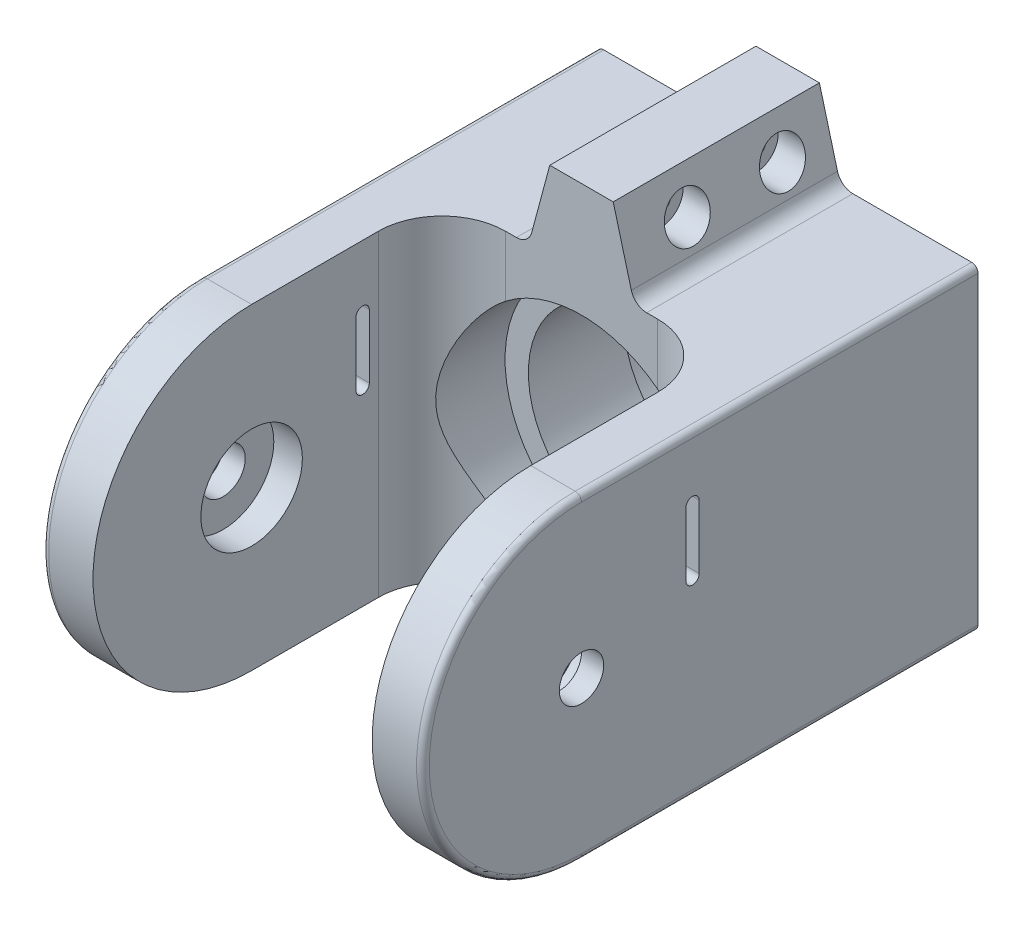
SolidWorks part; units mm, degrees
ref_plane "Front Plane" through (0, 0, 0) normal (0, 0, 1) x (1, 0, 0)
ref_plane "Top Plane" through (0, 0, 0) normal (0, 1, 0) x (1, 0, 0)
ref_plane "Right Plane" through (0, 0, 0) normal (1, 0, 0) x (0, 0, -1)
sketch "Sketch1" plane through (0, 0, 0) normal (0, 0, 1) x (1, 0, 0)
  circle A2 centre (0, 0) radius 31.75
  circle A4 centre (0, 0) radius 39.1
  circle A5 centre (0, 0) radius 38.1 construction
  dimension "D1" = 1
  dimension "D2" = 63.5
extrude "Centre Hole for L2" add sketch "Sketch1" along normal blind 30 contours A4 | A2
sketch "Sketch2" plane through (0, 0, 30) normal (0, 0, 1) x (1, 0, 0)
  line L0 (0, 48.4974) -> (0, 0) construction
  line L5 (-60, 50) -> (-60, -50)
  line L12 (0, 0) -> (72.986, 0) construction
  line L16 (-60, 50) -> (60, 50)
  line L17 (60, 50) -> (60, -50)
  line L18 (-60, -50) -> (60, -50)
  circle A2 centre (0, 0) radius 39.1
  circle A3 centre (0, 0) radius 39.1 construction
  point P13 (0, 50)
  dimension "D1" = 60
  dimension "D2" = 100
extrude "Main Structure" add sketch "Sketch2" along normal blind 75 and the other way blind 50 separate body contours L5 L18 L17 L16 A2
sketch "Sketch3" plane through (-60, 0, 0) normal (-1, 0, 0) x (0, 0, 1)
  line L0 (105, 50) -> (105, -50) construction
  line L1 (105, 50) -> (105, -50)
  line L2 (-20, 50) -> (105, 50) construction
  arc A0 (105, 50) -> (105, -50) centre (105, 0) cw
extrude "Bearing Curve" add sketch "Sketch3" against normal blind 16 contours A0 L1
mirror "Upright Mirror" about plane through (0, 0, 0) normal (1, 0, 0) of "Bearing Curve"
sketch "Sketch6" plane through (-60, 0, 0) normal (-1, 0, 0) x (0, 0, 1)
  circle A0 centre (105, 0) radius 7
  dimension "D1" = 14
extrude "Shaft Hole" cut sketch "Sketch6" against normal up to surface (104 mm away)
sketch "Sketch4" plane through (0, 50, 0) normal (0, 1, 0) x (1, 0, 0)
  line L0 (0, -110) -> (0, 20) construction
  line L1 (-44, -105) -> (44, -105) construction
  line L2 (-60, 20) -> (60, 20) construction
  line L3 (-44, -105) -> (-44, -65)
  line L4 (-24, -45) -> (24, -45)
  line L5 (-44, -105) -> (44, -105)
  line L6 (44, -105) -> (44, -65)
  arc A0 (-44, -65) -> (-24, -45) centre (-24, -65) cw
  arc A1 (44, -65) -> (24, -45) centre (24, -65) ccw
  point P17 (0, -105)
  point P20 (0, -45)
  dimension "D2" = 20
  dimension "D1" = 65
extrude "Wrist Cutout" cut sketch "Sketch4" against normal through all
sketch "Sketch9" plane through (-44, 0, 0) normal (1, 0, 0) x (0, 0, -1)
  circle A0 centre (-105, 0) radius 16
  dimension "D1" = 32
extrude "Bearing" cut sketch "Sketch9" against normal blind 9
mirror "Bearing Mirror" about plane through (0, 0, 0) normal (1, 0, 0) of "Bearing", "Shaft Hole"
sketch "Sketch10" plane through (0, 0, -20) normal (0, 0, -1) x (-1, 0, 0)
  line L0 (0, 50) -> (0, 75) construction
  line L1 (50, 50) -> (-50, 50) construction
  line L2 (10, 75) -> (-10, 75)
  line L3 (-10, 75) -> (-16.6987, 50)
  line L4 (-16.6987, 50) -> (16.6987, 50)
  line L5 (10, 75) -> (16.6987, 50)
  dimension "D1" = 25
  dimension "D2" = 10
  dimension "D3" = 75
extrude "Bolt Structure" add sketch "Sketch10" against normal up to surface (65 mm away) up to face at (0, -42.4919, 45)
sketch "Sketch11" plane through (0, 0, 0) normal (1, 0, 0) x (0, 0, -1)
  line L1 (-45, 62.5) -> (20, 62.5) construction
  line L2 (-45, 50) -> (-45, 75) construction
  line L3 (20, 75) -> (20, 50) construction
  circle A1 centre (5, 62.5) radius 3.1
  circle A2 centre (-25, 62.5) radius 3.1
  dimension "D1" = 6.2
  dimension "D2" = 15
  dimension "D3" = 30
extrude "Cut-Extrude6" cut sketch "Sketch11" against normal through all both and the other way through all
sketch "Sketch13" plane through (0, 0, 0) normal (1, 0, 0) x (0, 0, -1)
  circle A0 centre (5, 62.5) radius 7
  circle A1 centre (-25, 62.5) radius 7
  dimension "D1" = 14
extrude "Cut-Extrude8" cut sketch "Sketch13" along normal up to surface (8.3494 mm away) from offset 5
mirror "Mirror8" about plane through (0, 0, 0) normal (0, 1, 0) of "Cut-Extrude6", "Cut-Extrude8", "Bolt Structure"
fillet "Fillet3" radius 5 4 edges at (-16.6987, -50, 12.5) (16.6987, -50, 12.5) (-16.6987, 50, 12.5) (16.6987, 50, 12.5)
fillet "Fillet1" radius 2 6 edges at (-60, 50, 42.5) (-60, -50, 42.5) (60, -50, 42.5) (60, 50, 42.5) (-60, 0, 155) (60, 0, 155)
sketch "Sketch14" plane through (-60, 0, 0) normal (-1, 0, 0) x (0, 0, 1)
  line L0 (70, 30) -> (70, 10) construction
  line L1 (72.1, 30) -> (72.1, 10)
  line L2 (67.9, 30) -> (67.9, 10)
  arc A0 (72.1, 30) -> (67.9, 30) centre (70, 30) ccw
  arc A1 (67.9, 10) -> (72.1, 10) centre (70, 10) ccw
  point P2 (70, 20)
  dimension "D1" = 4.2
  dimension "D2" = 20
  dimension "D3" = 10
  dimension "D4" = 70
extrude "Tensioner Slot" cut sketch "Sketch14" against normal up to surface (104 mm away)
mirror "Mirror9" about plane through (0, 0, 0) normal (1, 0, 0) of "Tensioner Slot"
